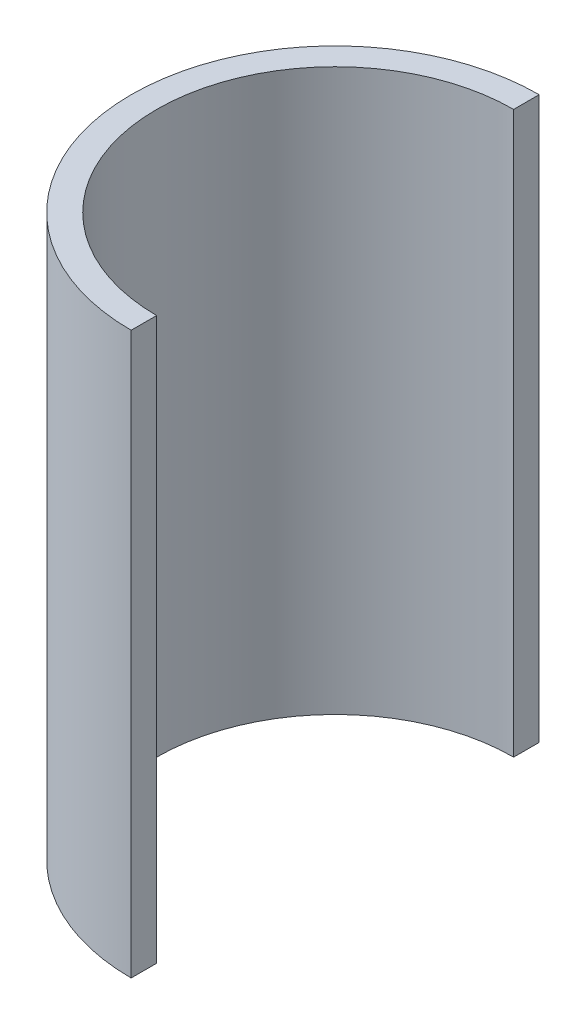
SolidWorks part; units mm, degrees
ref_plane "Front Plane" through (0, 0, 0) normal (0, 0, 1) x (1, 0, 0)
ref_plane "Top Plane" through (0, 0, 0) normal (0, 1, 0) x (1, 0, 0)
ref_plane "Right Plane" through (0, 0, 0) normal (1, 0, 0) x (0, 0, -1)
sketch "Sketch1" plane through (0, 0, 0) normal (0, 1, 0) x (1, 0, 0)
  line L0 (0, 40) -> (0, 35)
  line L1 (0, -35) -> (0, -40)
  arc A0 (0, 40) -> (0, -40) centre (0, 0) ccw
  arc A1 (0, 35) -> (0, -35) centre (0, 0) ccw
  circle A3 centre (0, 0) radius 35 construction
  circle A4 centre (0, 0) radius 40 construction
  point P4 (38.2522, 11.6949)
  point P7 (35, 0)
  dimension "D1" = 5
extrude "Boss-Extrude1" add sketch "Sketch1" along normal blind 110
